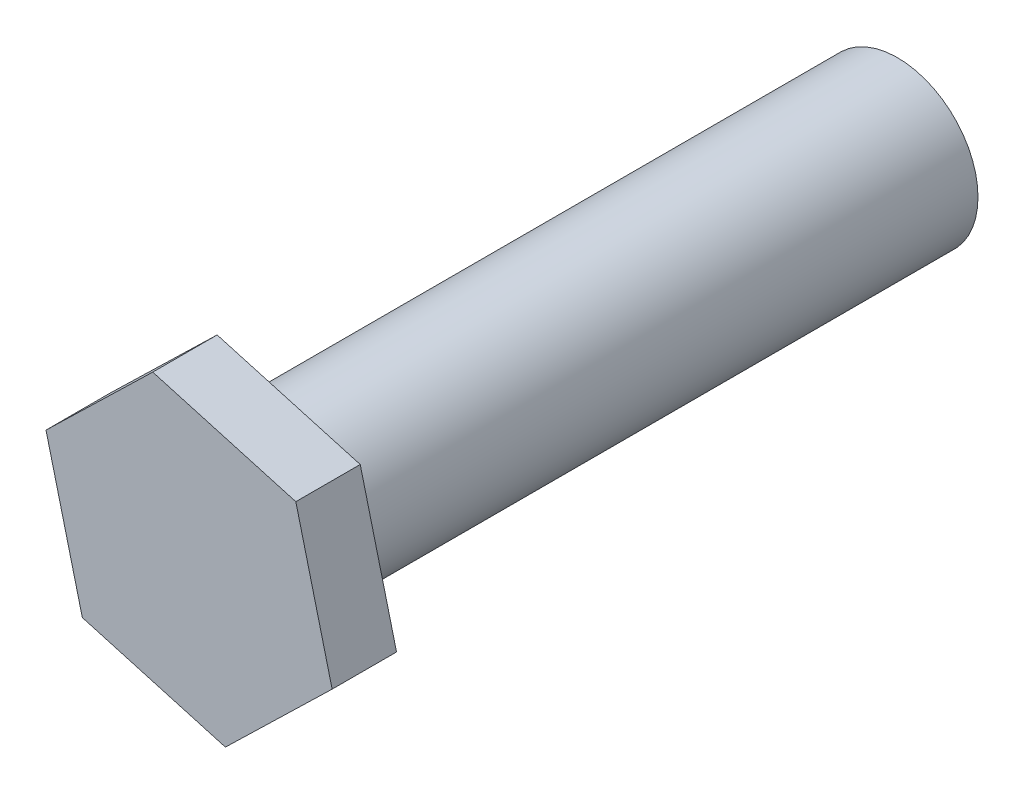
SolidWorks part; units mm, degrees
ref_plane "Спереди" through (0, 0, 0) normal (0, 0, 1) x (1, 0, 0)
ref_plane "Сверху" through (0, 0, 0) normal (0, 1, 0) x (1, 0, 0)
ref_plane "Справа" through (0, 0, 0) normal (1, 0, 0) x (0, 0, -1)
sketch "Эскиз1" plane through (0, 0, 0) normal (0, 0, 1) x (1, 0, 0)
  circle A0 centre (0, 0) radius 2.5
  dimension "D1" = 5
extrude "Бобышка-Вытянуть1" add sketch "Эскиз1" along normal blind 20
sketch "Эскиз3" plane through (0, 0, 20) normal (0, 0, 1) x (1, 0, 0)
  line L1 (3.315, 3.2163) -> (-1.1279, 4.479)
  line L2 (-1.1279, 4.479) -> (-4.4429, 1.2627)
  line L3 (-4.4429, 1.2627) -> (-3.315, -3.2163)
  line L4 (-3.315, -3.2163) -> (1.1279, -4.479)
  line L5 (1.1279, -4.479) -> (4.4429, -1.2627)
  line L6 (4.4429, -1.2627) -> (3.315, 3.2163)
  circle A0 centre (0, 0) radius 4 construction
  dimension "D1" = 8
extrude "Бобышка-Вытянуть2" add sketch "Эскиз3" along normal blind 2
